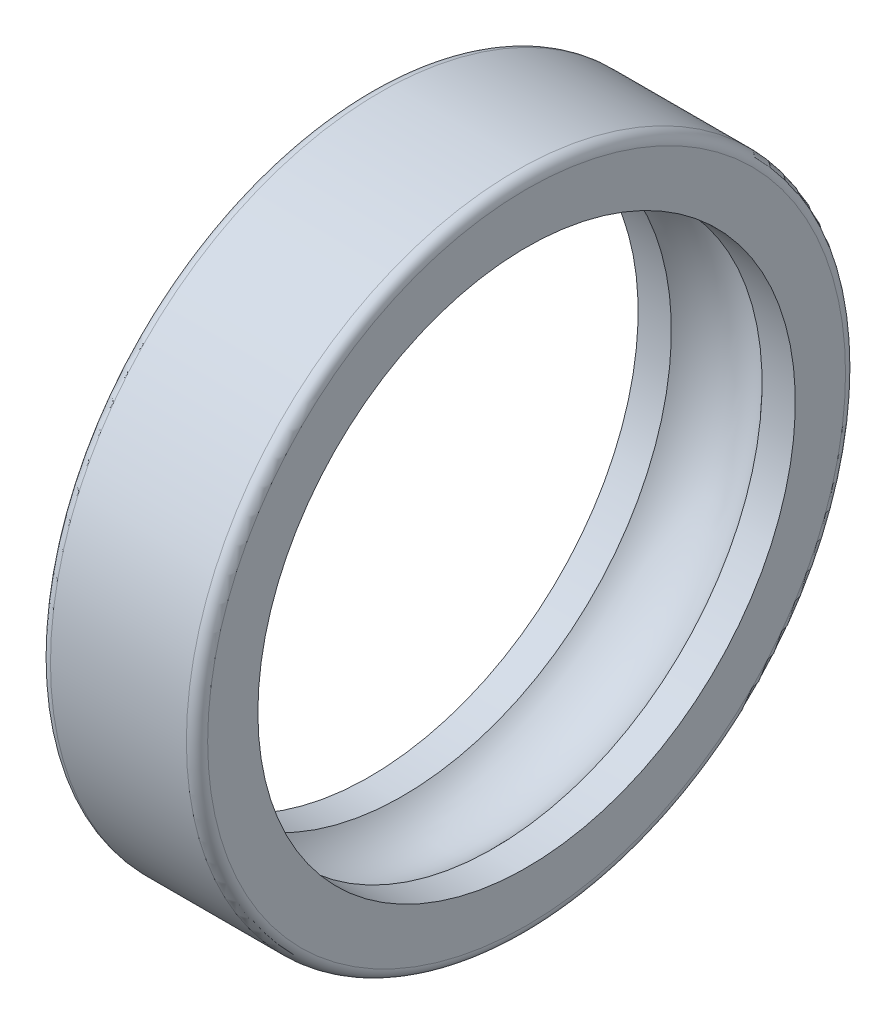
SolidWorks part; units mm, degrees
ref_plane "Front Plane" through (0, 0, 0) normal (0, 0, 1) x (1, 0, 0)
ref_plane "Top Plane" through (0, 0, 0) normal (0, 1, 0) x (1, 0, 0)
ref_plane "Right Plane" through (0, 0, 0) normal (1, 0, 0) x (0, 0, -1)
sketch "Sketch1" plane through (0, 0, 0) normal (0, 0, 1) x (1, 0, 0)
  line L0 (-25.3585, 0) -> (48.5277, 0) construction
  line L1 (0, 0) -> (0, 53) construction
  line L2 (-15.5, 65) -> (15.5, 65)
  line L3 (-15.5, 65) -> (-15.5, 53)
  line L4 (-15.5, 53) -> (-8.9443, 53)
  line L5 (15.5, 65) -> (15.5, 53)
  line L6 (-15.5, 65) -> (15.5, 53) construction
  line L7 (-15.5, 53) -> (15.5, 65) construction
  line L8 (8.9443, 53) -> (15.5, 53)
  arc A0 (-8.9443, 53) -> (8.9443, 53) centre (0, 45) cw
  point P3 (0, 59)
  dimension "D4" = 12
  dimension "D1" = 31
  dimension "D2" = 53
  dimension "D3" = 65
  dimension "D5" = 8
revolve "Revolve1" add sketch "Sketch1" angle 360 about L0
fillet "Fillet1" radius 2.1 2 edges at (15.5, 0, 65) (-15.5, 0, 65)
scale "Scale1" scale about centroid uniform scaling yes scale factor 0.35
